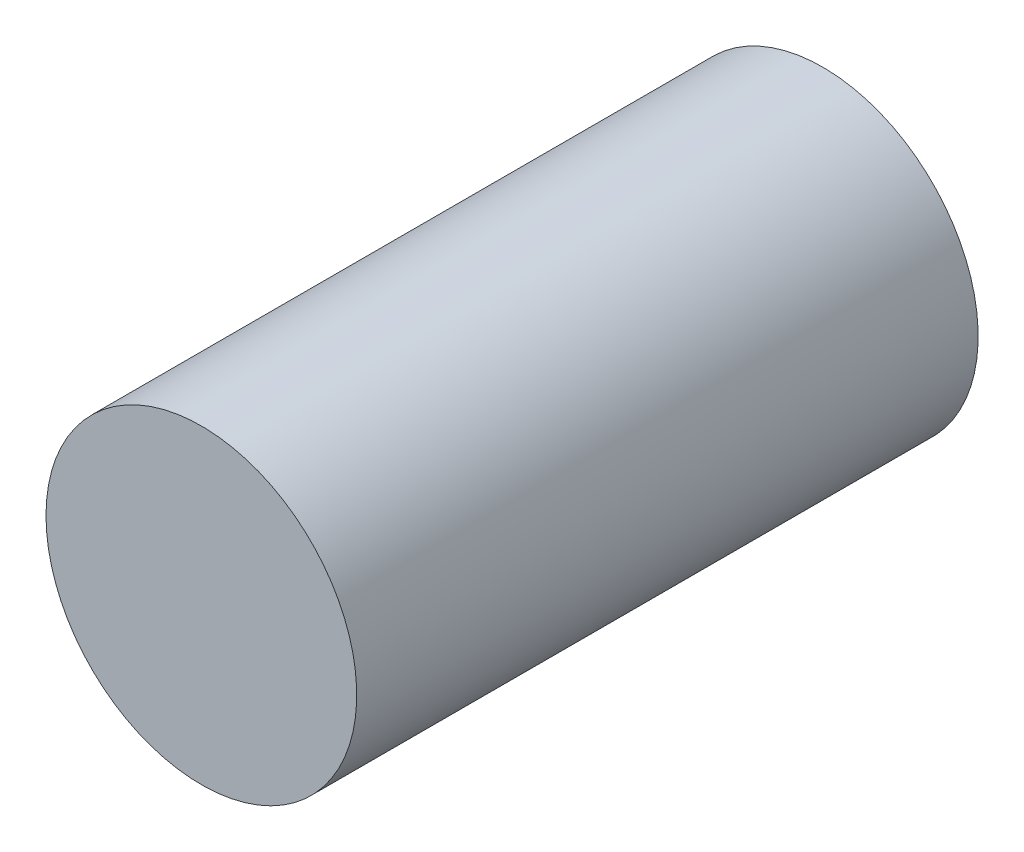
SolidWorks part; units mm, degrees
ref_plane "Front Plane" through (0, 0, 0) normal (0, 0, 1) x (1, 0, 0)
ref_plane "Top Plane" through (0, 0, 0) normal (0, 1, 0) x (1, 0, 0)
ref_plane "Right Plane" through (0, 0, 0) normal (1, 0, 0) x (0, 0, -1)
sketch "Sketch1" plane through (0, 0, 0) normal (0, 0, 1) x (1, 0, 0)
  circle A0 centre (0, 0) radius 152.4
extrude "Boss-Extrude1" add sketch "Sketch1" along normal blind 609.6
